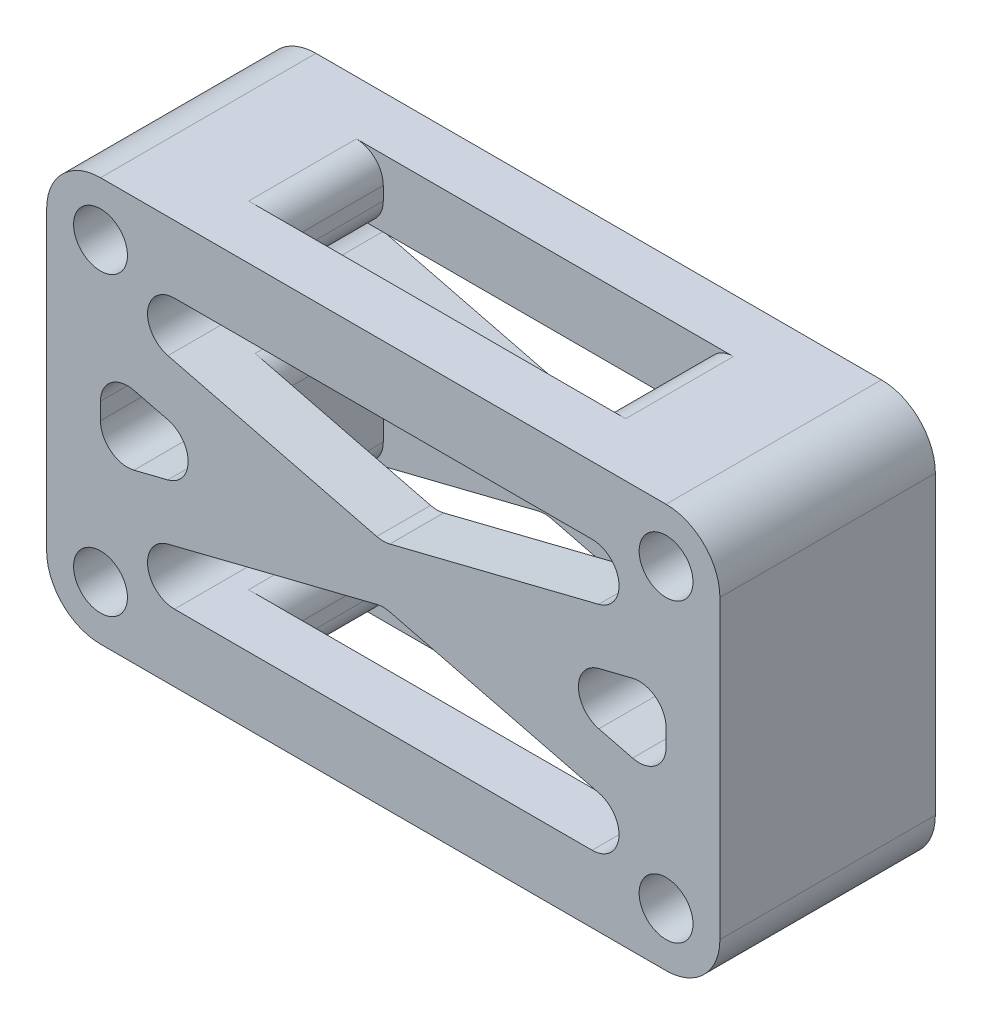
SolidWorks part; units mm, degrees
material "ABS"
ref_plane "Front" through (0, 0, 0) normal (0, 0, 1) x (1, 0, 0)
ref_plane "Top" through (0, 0, 0) normal (0, 1, 0) x (1, 0, 0)
ref_plane "Right" through (0, 0, 0) normal (1, 0, 0) x (0, 0, -1)
sketch "草图1" plane through (0, 0, 0) normal (0, 0, 1) x (1, 0, 0)
  line L1 (-12.5, -7.5) -> (12.5, -7.5)
  line L2 (-12.5, -7.5) -> (-12.5, 7.5)
  line L3 (-12.5, 7.5) -> (12.5, 7.5)
  line L4 (12.5, -7.5) -> (12.5, 7.5)
  line L5 (0, 7.5) -> (0, -7.5) construction
  line L6 (-12.5, 0) -> (12.5, 0) construction
  point P0 (0, 0)
  dimension "D1" = 15
  dimension "D2" = 25
extrude "凸台-拉伸1" add sketch "草图1" along normal blind 8
sketch "草图2" plane through (0, 0, 8) normal (0, 0, 1) x (1, 0, 0)
  line L0 (-0.2425, -1.0914) -> (-7.9963, -3.0299) construction
  line L1 (7.9963, -3.0299) -> (0.2425, -1.0914) construction
  line L2 (-0.2425, -1.0914) -> (-7.9963, -3.0299)
  line L3 (7.9963, -3.0299) -> (0.2425, -1.0914)
  line L4 (-1.5989, 0) -> (2.2438, 0) construction
  line L5 (7.7538, 5) -> (-7.7538, 5)
  line L6 (7.9963, 3.0299) -> (0.2425, 1.0914)
  line L7 (-0.2425, 1.0914) -> (-7.9963, 3.0299)
  line L8 (0, 0.633) -> (0, -0.5198) construction
  line L9 (-9.2575, -1.2836) -> (-8.0037, -0.9701)
  line L10 (-9.2575, 1.2836) -> (-8.0037, 0.9701)
  line L11 (10.5, 0.3134) -> (10.5, -0.3134)
  line L12 (7.7538, -5) -> (-7.7538, -5) construction
  line L13 (7.7538, -5) -> (-7.7538, -5)
  line L14 (12.5, -7.5) -> (12.5, 7.5) construction
  line L15 (-10.5, 0.3134) -> (-10.5, -0.3134)
  line L16 (9.2575, 1.2836) -> (8.0037, 0.9701)
  line L17 (9.2575, -1.2836) -> (8.0037, -0.9701)
  arc A0 (0.2425, -1.0914) -> (-0.2425, -1.0914) centre (0, -2.0616) ccw construction
  arc A1 (0.2425, -1.0914) -> (-0.2425, -1.0914) centre (0, -2.0616) ccw
  arc A2 (-7.9963, -3.0299) -> (-7.7538, -5) centre (-7.7538, -4) ccw construction
  arc A3 (7.7538, -5) -> (7.9963, -3.0299) centre (7.7538, -4) ccw construction
  arc A4 (-7.9963, -3.0299) -> (-7.7538, -5) centre (-7.7538, -4) ccw
  arc A5 (7.7538, -5) -> (7.9963, -3.0299) centre (7.7538, -4) ccw
  arc A6 (0.2425, 1.0914) -> (-0.2425, 1.0914) centre (0, 2.0616) cw
  arc A7 (8.0037, 0.9701) -> (8.0037, -0.9701) centre (8.2462, 0) ccw
  arc A8 (7.7538, 5) -> (7.9963, 3.0299) centre (7.7538, 4) cw
  arc A9 (-7.9963, 3.0299) -> (-7.7538, 5) centre (-7.7538, 4) cw
  arc A10 (10.5, -0.3134) -> (9.2575, -1.2836) centre (9.5, -0.3134) cw
  arc A11 (9.2575, 1.2836) -> (10.5, 0.3134) centre (9.5, 0.3134) cw
  arc A12 (-9.2575, 1.2836) -> (-10.5, 0.3134) centre (-9.5, 0.3134) ccw
  arc A13 (-10.5, -0.3134) -> (-9.2575, -1.2836) centre (-9.5, -0.3134) ccw
  arc A14 (-8.0037, 0.9701) -> (-8.0037, -0.9701) centre (-8.2462, 0) cw
  point P6 (-10.4472, 4.1056)
  point P7 (9.5528, -5.8944)
  point P8 (-9.5528, 5.8944)
  point P9 (10.4472, -4.1056)
  point P10 (-9.5528, -5.8944)
  point P11 (10.4472, 4.1056)
  point P12 (-10.4472, -4.1056)
  point P13 (9.5528, 5.8944)
  point P14 (-10.5211, -6.8779)
  point P15 (11.4789, 5.1221)
  point P16 (-11.4789, 5.1221)
  point P17 (10.5211, -6.8779)
  point P18 (-11.4789, -5.1221)
  point P19 (10.5211, 6.8779)
  point P20 (-10.5211, 6.8779)
  point P21 (11.4789, -5.1221)
  dimension "D2" = 1
  dimension "D1" = 2
fillet "圆角4" radius 2 4 edges at (-12.5, 7.5, 4) (12.5, -7.5, 4) (12.5, 7.5, 4) (-12.5, -7.5, 4)
extrude "切除-拉伸3" cut sketch "草图2" against normal blind 10
sketch "草图3" plane through (0, 0, 8) normal (0, 0, 1) x (1, 0, 0)
  line L0 (0, 2.5569) -> (0, -1.9542) construction
  line L1 (-2.779, 0) -> (2.7367, 0) construction
  circle A0 centre (-10.5, 5.5) radius 1
  circle A1 centre (10.5, 5.5) radius 1
  circle A2 centre (10.5, -5.5) radius 1
  circle A3 centre (-10.5, -5.5) radius 1
  dimension "D1" = 2
extrude "切除-拉伸4" cut sketch "草图3" against normal blind 10
sketch "草图4" plane through (0, -7.5, 0) normal (0, -1, 0) x (1, 0, 0)
  line L1 (-6, 2) -> (6, 2)
  line L2 (-6, 2) -> (-6, 6)
  line L3 (-6, 6) -> (6, 6)
  line L4 (6, 2) -> (6, 6)
  line L5 (-6, 2) -> (6, 6) construction
  line L6 (-6, 6) -> (6, 2) construction
  point P0 (0, 4)
  point P5 (-0.0364, 3.5054)
  point P6 (0, 4)
  point P7 (0, 4)
  dimension "D1" = 12
  dimension "D2" = 4
extrude "切除-拉伸5" cut sketch "草图4" against normal through all both and the other way through all
fillet "圆角6" radius 1 12 edges at (6, 5, 4) (-6, 7.5, 4) (6, 7.5, 4) (-6, 5, 4) (6, -2.5308, 4) (-6, 2.5308, 4) (6, 2.5308, 4) (-6, -2.5308, 4) (6, -7.5, 4) (-6, -5, 4) (6, -5, 4) (-6, -7.5, 4)
